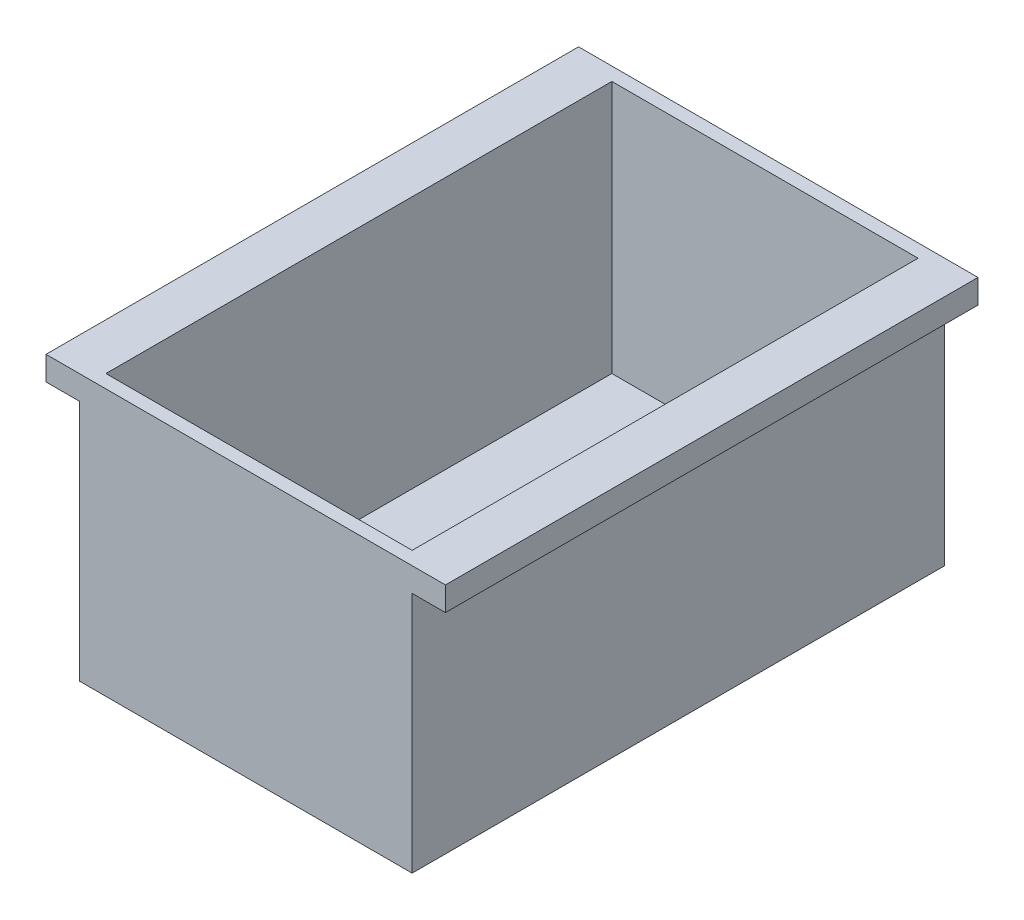
SolidWorks part; units mm, degrees
ref_plane "Front Plane" through (0, 0, 0) normal (0, 0, 1) x (1, 0, 0)
ref_plane "Top Plane" through (0, 0, 0) normal (0, 1, 0) x (1, 0, 0)
ref_plane "Right Plane" through (0, 0, 0) normal (1, 0, 0) x (0, 0, -1)
sketch "Sketch1" plane through (0, 0, 0) normal (0, 1, 0) x (1, 0, 0)
  line L1 (0, 0) -> (63.5, 0)
  line L2 (0, 0) -> (0, 101.6)
  line L3 (0, 101.6) -> (63.5, 101.6)
  line L4 (63.5, 0) -> (63.5, 101.6)
  dimension "D1" = 63.5
  dimension "D2" = 101.6
extrude "Boss-Extrude1" add sketch "Sketch1" along normal blind 50.8
shell "Shell1" thickness 2.54
sketch "Sketch2" plane through (0, 50.8, 0) normal (0, 1, 0) x (1, 0, 0)
  line L1 (0, 101.6) -> (-6.35, 101.6)
  line L2 (0, 101.6) -> (0, 0)
  line L3 (0, 0) -> (-6.35, 0)
  line L4 (-6.35, 101.6) -> (-6.35, 0)
  line L5 (63.5, 101.6) -> (69.85, 101.6)
  line L6 (63.5, 101.6) -> (63.5, 0)
  line L7 (63.5, 0) -> (69.85, 0)
  line L8 (69.85, 101.6) -> (69.85, 0)
  dimension "D1" = 6.35
  dimension "D2" = 6.35
extrude "Boss-Extrude2" add sketch "Sketch2" against normal blind 4.572
